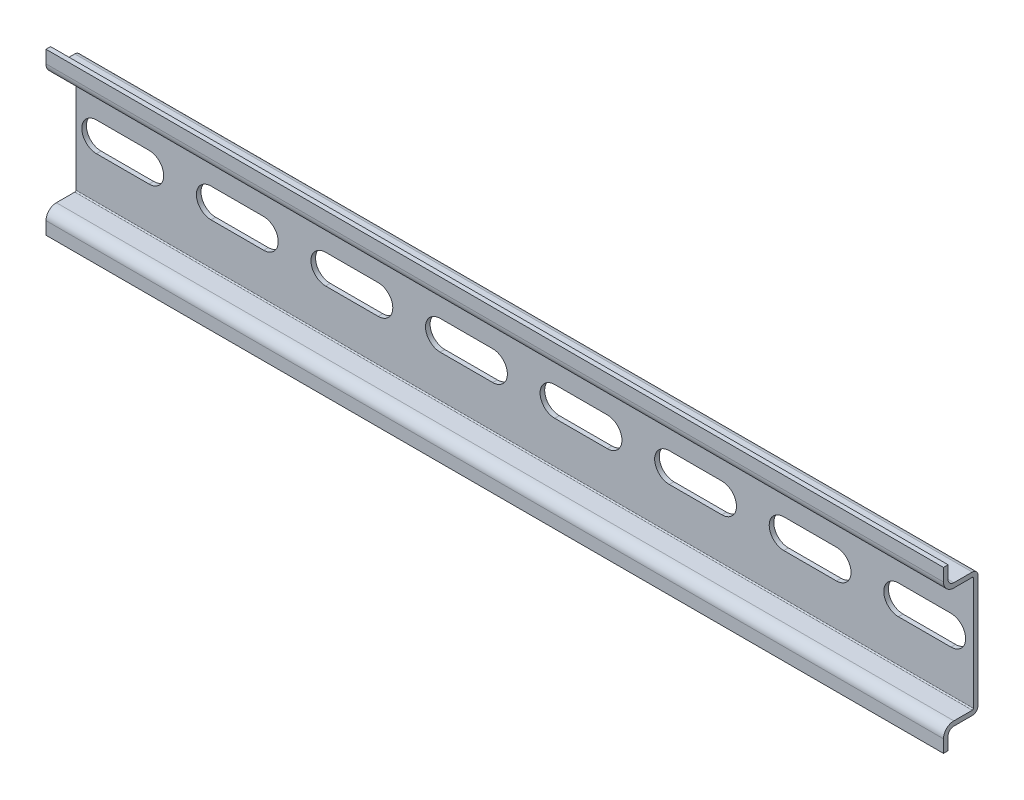
SolidWorks part; units mm, degrees
ref_plane "Front Plane" through (0, 0, 0) normal (0, 0, 1) x (1, 0, 0)
ref_plane "Top Plane" through (0, 0, 0) normal (0, 1, 0) x (1, 0, 0)
ref_plane "Right Plane" through (0, 0, 0) normal (1, 0, 0) x (0, 0, -1)
sketch "Sketch1" plane through (0, 0, 0) normal (0, 1, 0) x (1, 0, 0)
  line L0 (-250, 0) -> (250, 0)
  point P3 (0, 0)
  dimension "D1" = 500
other "Structural Member1"
ref_plane "Plane1" through (-250, 0, 0) normal (1, 0, 0) x (0, 0, -1)
sketch "Sketch2" plane through (-250, 0, 0) normal (1, 0, 0) x (0, 0, -1)
  line L0 (0, 12.25) -> (0, -12.25)
  line L1 (-1.25, 13.5) -> (-5.25, 13.5)
  line L2 (-6.5, 14.75) -> (-6.5, 17.5)
  line L3 (0, 0) -> (-1, 0) construction
  line L4 (-6.5, -14.75) -> (-6.5, -17.5)
  line L5 (-1.25, -13.5) -> (-5.25, -13.5)
  line L6 (-7.5, 14.75) -> (-7.5, 17.5)
  line L7 (-1.25, 12.5) -> (-5.25, 12.5)
  line L8 (-1, 12.25) -> (-1, -12.25)
  line L9 (-1.25, -12.5) -> (-5.25, -12.5)
  line L10 (-7.5, -14.75) -> (-7.5, -17.5)
  line L11 (-6.5, 17.5) -> (-7.5, 17.5)
  line L12 (-6.5, -17.5) -> (-7.5, -17.5)
  arc A0 (-5.25, 13.5) -> (-6.5, 14.75) centre (-5.25, 14.75) cw
  arc A1 (-6.5, -14.75) -> (-5.25, -13.5) centre (-5.25, -14.75) cw
  arc A2 (0, -12.25) -> (-1.25, -13.5) centre (-1.25, -12.25) cw
  arc A3 (0, 12.25) -> (-1.25, 13.5) centre (-1.25, 12.25) ccw
  arc A4 (-5.25, 12.5) -> (-7.5, 14.75) centre (-5.25, 14.75) cw
  arc A5 (-1, 12.25) -> (-1.25, 12.5) centre (-1.25, 12.25) ccw
  arc A6 (-1, -12.25) -> (-1.25, -12.5) centre (-1.25, -12.25) cw
  arc A7 (-7.5, -14.75) -> (-5.25, -12.5) centre (-5.25, -14.75) cw
  point P3 (0, 0)
  point P12 (-6.5, 13.5)
  point P15 (-6.5, -13.5)
  point P18 (0, -13.5)
  point P21 (0, 13.5)
  point P36 (0, 0)
  dimension "D4" = 1.25
  dimension "D1" = 35
  dimension "D2" = 27
  dimension "D3" = 7.5
  dimension "D5" = 1
sketch "Sketch3" plane through (0, 0, 0) normal (0, 0, 1) x (1, 0, 0)
  line L0 (-241.745, 0) -> (-230.315, 0) construction
  line L1 (-241.745, 3.175) -> (-230.315, 3.175)
  line L2 (-241.745, -3.175) -> (-230.315, -3.175)
  line L3 (-250, 12.25) -> (-250, -12.25) construction
  arc A0 (-241.745, 3.175) -> (-241.745, -3.175) centre (-241.745, 0) ccw
  arc A1 (-230.315, -3.175) -> (-230.315, 3.175) centre (-230.315, 0) ccw
  point P2 (-236.03, 0)
  dimension "D1" = 5.08
  dimension "D2" = 17.78
  dimension "D3" = 3.175
extrude "Cut-Extrude1" cut sketch "Sketch3" along normal up to next
pattern_linear "LPattern1" count 196 spacing 24.892 along (1, 0, 0) of "Cut-Extrude1"
sketch "Sketch4" plane through (0, 0, 7.5) normal (0, 0, 1) x (1, 0, 0)
  line L0 (250, 12.25) -> (250, -12.25) construction
  line L1 (-3947.5, 78.5136) -> (52.5, 78.5136)
  line L2 (-3947.5, 78.5136) -> (-3947.5, -104.3335)
  line L3 (-3947.5, -104.3335) -> (52.5, -104.3335)
  line L4 (52.5, 78.5136) -> (52.5, -104.3335)
  dimension "D1" = 197.5
  dimension "D2" = 4000
extrude "Cut-Extrude2" cut sketch "Sketch4" against normal blind 140
sketch "Sketch5" plane through (0, 0, 7.5) normal (0, 0, 1) x (1, 0, 0)
  line L1 (251.0095, 24.6089) -> (247.5, 24.6089)
  line L2 (251.0095, 24.6089) -> (251.0095, -30.9557)
  line L3 (251.0095, -30.9557) -> (247.5, -30.9557)
  line L4 (247.5, 24.6089) -> (247.5, -30.9557)
  line L5 (52.5, 12.25) -> (52.5, -12.25) construction
  dimension "D1" = 195
extrude "Cut-Extrude3" cut sketch "Sketch5" against normal blind 140
equation "\"D1@LPattern1\" = \"RD1@Annotations\" + 1"
